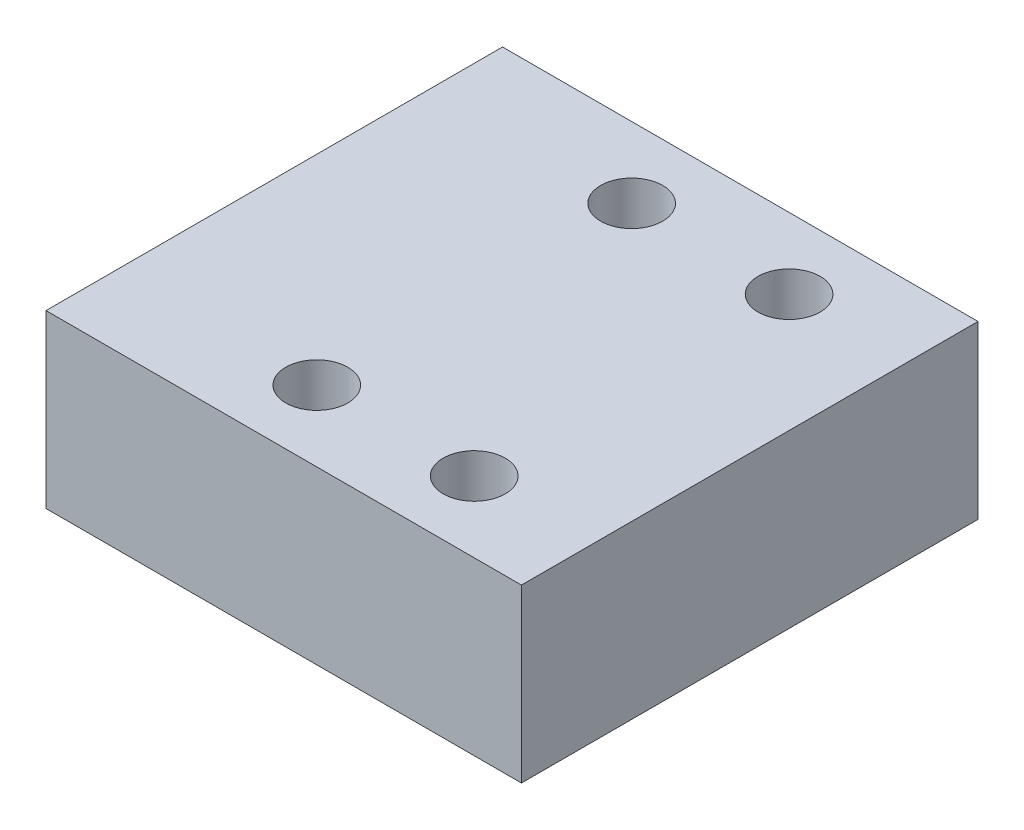
SolidWorks part; units mm, degrees
ref_plane "Front Plane" through (0, 0, 0) normal (0, 0, 1) x (1, 0, 0)
ref_plane "Top Plane" through (0, 0, 0) normal (0, 1, 0) x (1, 0, 0)
ref_plane "Right Plane" through (0, 0, 0) normal (1, 0, 0) x (0, 0, -1)
sketch "Sketch1" plane through (0, 0, 0) normal (0, 1, 0) x (1, 0, 0)
  line L0 (9.0422, 4.0743) -> (-29.3118, 4.0743) construction
  line L1 (-29.3118, 22.4893) -> (9.0422, 22.4893)
  line L2 (-29.3118, 22.4893) -> (-29.3118, -14.3407)
  line L3 (-29.3118, -14.3407) -> (9.0422, -14.3407)
  line L4 (9.0422, 22.4893) -> (9.0422, -14.3407)
  circle A0 centre (-0.4828, 16.7743) radius 2.5019
  circle A1 centre (-13.1828, 16.7743) radius 2.5019
  circle A2 centre (-0.4828, -8.6257) radius 2.5019
  circle A3 centre (-13.1828, -8.6257) radius 2.5019
  dimension "D3" = 25.4
  dimension "D4" = 5.0038
  dimension "D5" = 12.7
  dimension "D6" = 5.0038
  dimension "D7" = 9.525
  dimension "D1" = 38.354
  dimension "D2" = 36.83
extrude "Boss-Extrude1" add sketch "Sketch1" along normal blind 13.8303
